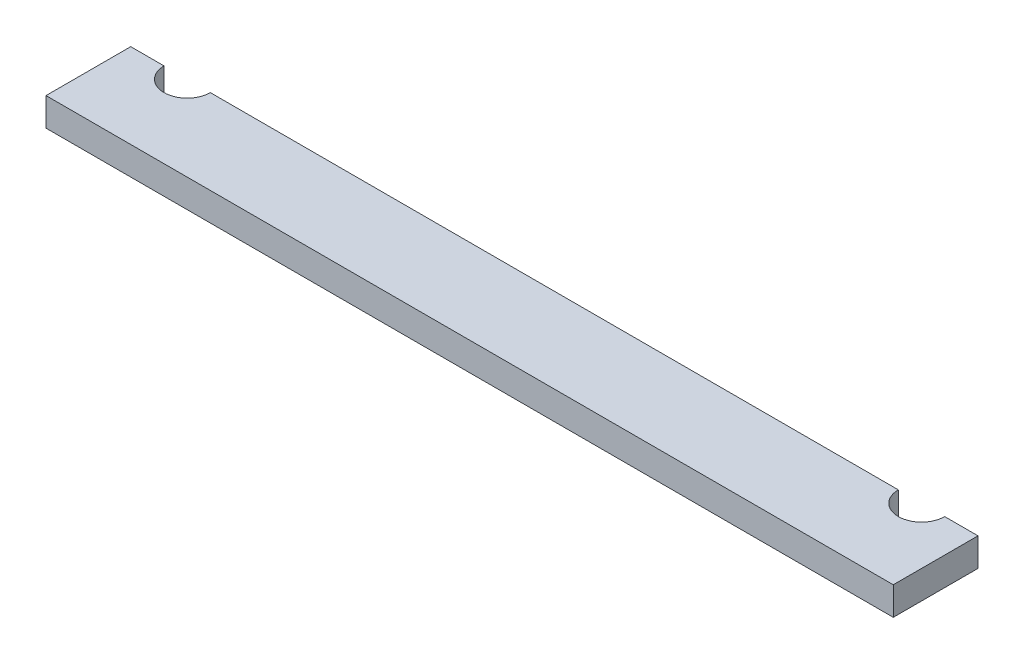
SolidWorks part; units mm, degrees
ref_plane "Front Plane" through (0, 0, 0) normal (0, 0, 1) x (1, 0, 0)
ref_plane "Top Plane" through (0, 0, 0) normal (0, 1, 0) x (1, 0, 0)
ref_plane "Right Plane" through (0, 0, 0) normal (1, 0, 0) x (0, 0, -1)
sketch "Sketch1" plane through (0, 0, 0) normal (0, 1, 0) x (1, 0, 0)
  line L0 (75, 0) -> (75, -15) construction
  line L1 (0, 0) -> (150, 0)
  line L2 (0, 0) -> (0, -15)
  line L3 (0, -15) -> (150, -15)
  line L4 (150, 0) -> (150, -15)
  circle A0 centre (10, 0) radius 4.1
  circle A1 centre (140, 0) radius 4.1
  dimension "D3" = 8.2
  dimension "D1" = 150
  dimension "D2" = 15
  dimension "D4" = 130
extrude "Boss-Extrude1" add sketch "Sketch1" along normal blind 5 contours L0 L1 A0 L2 L3 | L1 L0 L3 L4 A1
